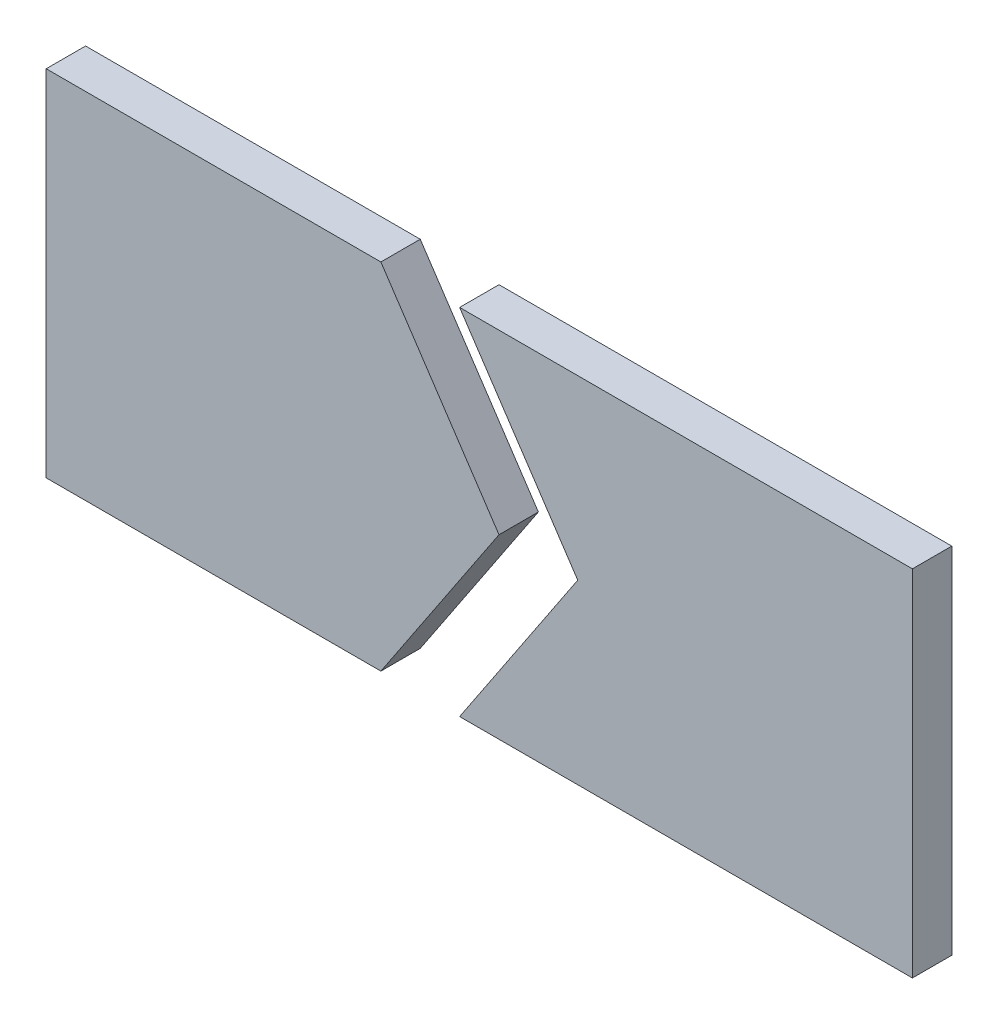
SolidWorks part; units mm, degrees
ref_plane "Plan de face" through (0, 0, 0) normal (0, 0, 1) x (1, 0, 0)
ref_plane "Plan de dessus" through (0, 0, 0) normal (0, 1, 0) x (1, 0, 0)
ref_plane "Plan de droite" through (0, 0, 0) normal (1, 0, 0) x (0, 0, -1)
sketch "Esquisse1" plane through (0, 0, 0) normal (0, 0, 1) x (1, 0, 0)
  line L0 (-0.8, 0) -> (0.8, 0) construction
  line L1 (0, 0.6665) -> (0, -0.6887) construction
  line L2 (-1.1, 0.45) -> (-0.5, 0.45)
  line L3 (-1.1, 0.45) -> (-1.1, -0.45)
  line L4 (-1.1, -0.45) -> (-0.5, -0.45)
  line L5 (-0.5, 0.45) -> (-0.5, -0.45) construction
  line L6 (-1.1, 0.45) -> (-0.5, -0.45) construction
  line L7 (-1.1, -0.45) -> (-0.5, 0.45) construction
  line L8 (1.1, 0.45) -> (0.5, 0.45)
  line L9 (1.1, 0.45) -> (1.1, -0.45)
  line L10 (1.1, -0.45) -> (0.5, -0.45)
  line L11 (0.5, 0.45) -> (0.5, -0.45) construction
  line L12 (-0.5, 0.45) -> (-0.25, 0.45)
  line L13 (-0.25, 0.45) -> (0.05, 0)
  line L14 (-0.25, -0.45) -> (0.05, 0)
  line L15 (-0.5, -0.45) -> (-0.25, -0.45)
  line L16 (0.5, 0.45) -> (-0.05, 0.45)
  line L17 (-0.05, 0.45) -> (0.25, 0)
  line L18 (-0.05, -0.45) -> (0.25, 0)
  line L19 (0.5, -0.45) -> (-0.05, -0.45)
  point P3 (0, 0)
  point P20 (0, 0)
  dimension "D1" = 0.6
  dimension "D2" = 0.9
  dimension "D3" = 1.6
  dimension "D4" = 0.55
  dimension "D5" = 0.3
  dimension "D6" = 0.2
  dimension "D7" = 0.1664
  dimension "D8" = 0.55
  dimension "D9" = 0.85
  dimension "D10" = 0.85
extrude "Boss.-Extru.1" add sketch "Esquisse1" along normal blind 0.1
